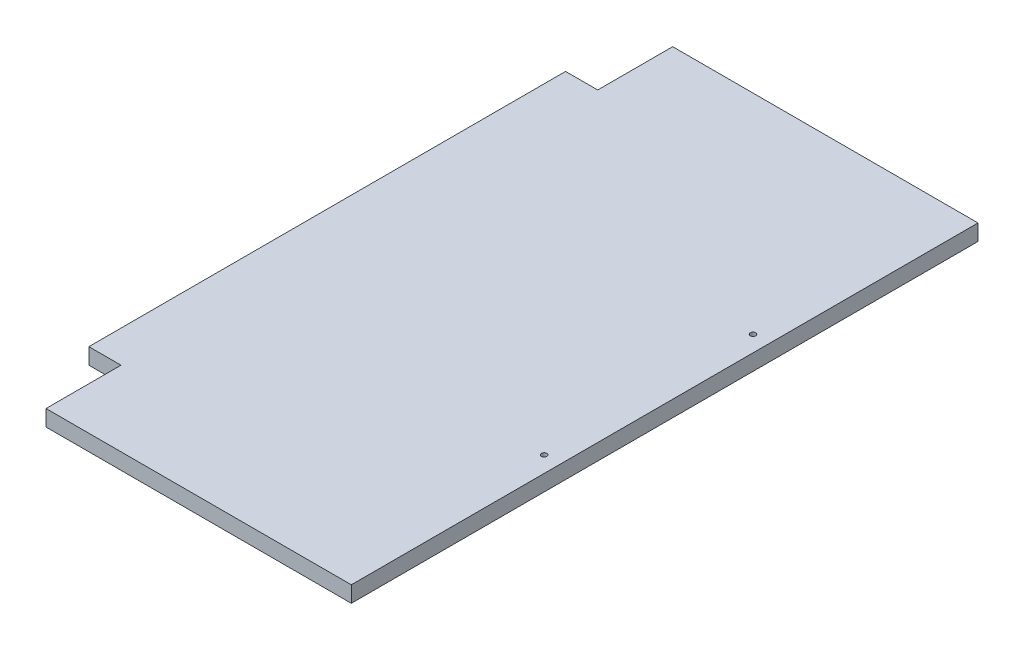
SolidWorks part; units mm, degrees
material "Balsa"
ref_plane "Front Plane" through (0, 0, 0) normal (0, 0, 1) x (1, 0, 0)
ref_plane "Top Plane" through (0, 0, 0) normal (0, 1, 0) x (1, 0, 0)
ref_plane "Right Plane" through (0, 0, 0) normal (1, 0, 0) x (0, 0, -1)
sketch "Sketch1" plane through (0, 0, 0) normal (0, 1, 0) x (1, 0, 0)
  line L0 (0, 0) -> (38.1, 0)
  line L1 (38.1, 0) -> (38.1, 88.9)
  line L2 (38.1, 88.9) -> (400.05, 88.9)
  line L3 (400.05, 88.9) -> (400.05, -654.05)
  line L4 (400.05, -654.05) -> (38.1, -654.05)
  line L5 (38.1, -654.05) -> (38.1, -565.15)
  line L6 (38.1, -565.15) -> (0, -565.15)
  line L7 (0, -565.15) -> (0, 0)
  circle A0 centre (381, -406.4) radius 3.175
  circle A1 centre (381, -158.75) radius 3.175
  dimension "D7" = 6.35
  dimension "D8" = 6.35
  dimension "D9" = 247.65
  dimension "D10" = 247.65
  dimension "D11" = 19.05
  dimension "D12" = 19.05
  dimension "D1" = 565.15
  dimension "D2" = 38.1
  dimension "D3" = 88.9
  dimension "D4" = 38.1
  dimension "D5" = 88.9
  dimension "D6" = 400.05
extrude "Boss-Extrude1" add sketch "Sketch1" along normal blind 19.05
